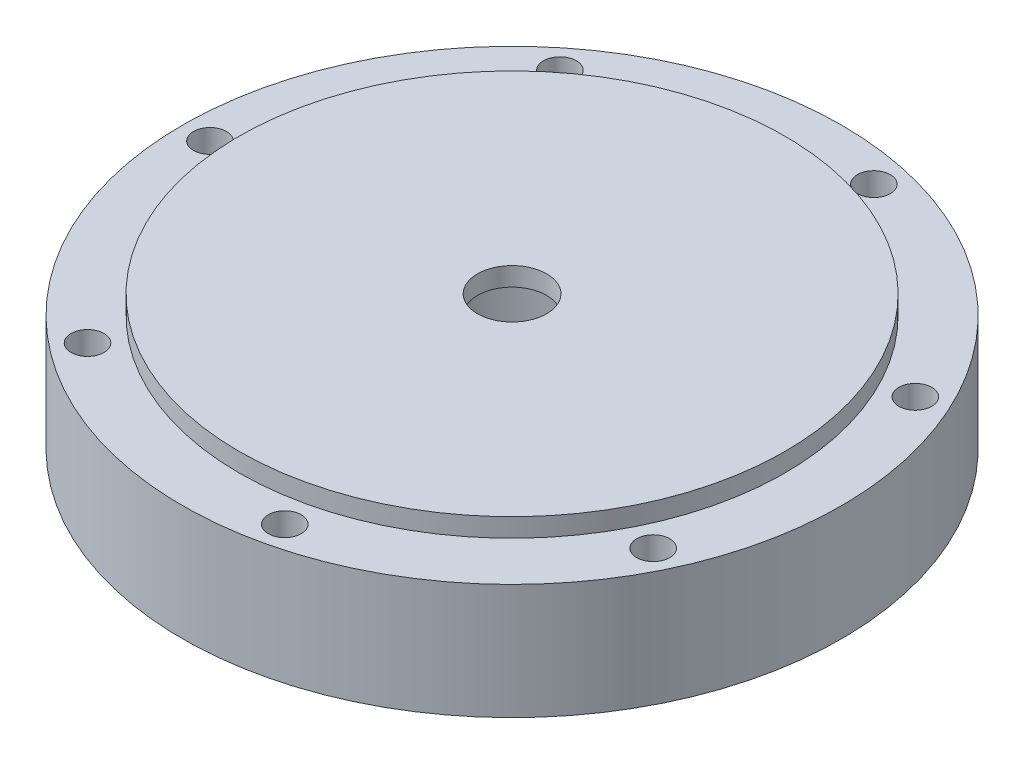
SolidWorks part; units mm, degrees
ref_plane "Alzado" through (0, 0, 0) normal (0, 0, 1) x (1, 0, 0)
ref_plane "Planta" through (0, 0, 0) normal (0, 1, 0) x (1, 0, 0)
ref_plane "Vista lateral" through (0, 0, 0) normal (1, 0, 0) x (0, 0, -1)
sketch "Croquis1" plane through (0, 0, 0) normal (0, 1, 0) x (1, 0, 0)
  circle A0 centre (0, 0) radius 30
  dimension "D1" = 60
extrude "Saliente-Extruir1" add sketch "Croquis1" along normal blind 10.5
sketch "Croquis2" plane through (0, 10.5, 0) normal (0, 1, 0) x (1, 0, 0)
  circle A0 centre (0, 0) radius 24.85
  dimension "D1" = 49.7
extrude "Saliente-Extruir2" add sketch "Croquis2" along normal blind 1.7
sketch "Croquis4" plane through (0, 10.5, 0) normal (0, 1, 0) x (1, 0, 0)
  circle A0 centre (-27.5, 0) radius 1.5
  circle A1 centre (-17.146, 21.5004) radius 1.5
  circle A2 centre (6.1193, 26.8105) radius 1.5
  circle A3 centre (24.7766, 11.9318) radius 1.5
  circle A4 centre (24.7766, -11.9318) radius 1.5
  circle A5 centre (6.1193, -26.8105) radius 1.5
  circle A6 centre (-17.146, -21.5004) radius 1.5
  point P17 (0, 0)
  dimension "D2" = 3
  dimension "D1" = 27.5
  dimension "D3" = 7
extrude "Cortar-Extruir1" cut sketch "Croquis4" against normal through all
sketch "Croquis5" plane through (0, 0, 0) normal (0, -1, 0) x (1, 0, 0)
  line L0 (-4.1352, 9.05) -> (4.1352, 9.05)
  line L1 (-4.1352, -9.05) -> (4.1352, -9.05)
  arc A0 (-4.5921, 8.9395) -> (-4.5921, -8.9395) centre (0, 0) ccw
  arc A1 (4.5921, -8.9395) -> (4.5921, 8.9395) centre (0, 0) ccw
  arc A2 (4.1352, -9.05) -> (4.5921, -8.9395) centre (4.1352, -8.05) ccw
  arc A3 (-4.1352, -9.05) -> (-4.5921, -8.9395) centre (-4.1352, -8.05) cw
  arc A4 (4.1352, 9.05) -> (4.5921, 8.9395) centre (4.1352, 8.05) cw
  arc A5 (-4.1352, 9.05) -> (-4.5921, 8.9395) centre (-4.1352, 8.05) ccw
  point P8 (4.3704, -9.05)
  dimension "D1" = 20.1
  dimension "D3" = 1
  dimension "D2" = 18.1
extrude "Cortar-Extruir2" cut sketch "Croquis5" against normal blind 10.5
sketch "Croquis6" plane through (0, 12.2, 0) normal (0, 1, 0) x (1, 0, 0)
  circle A0 centre (0, 0) radius 3.15
  dimension "D1" = 6.3
extrude "Cortar-Extruir3" cut sketch "Croquis6" against normal through all
